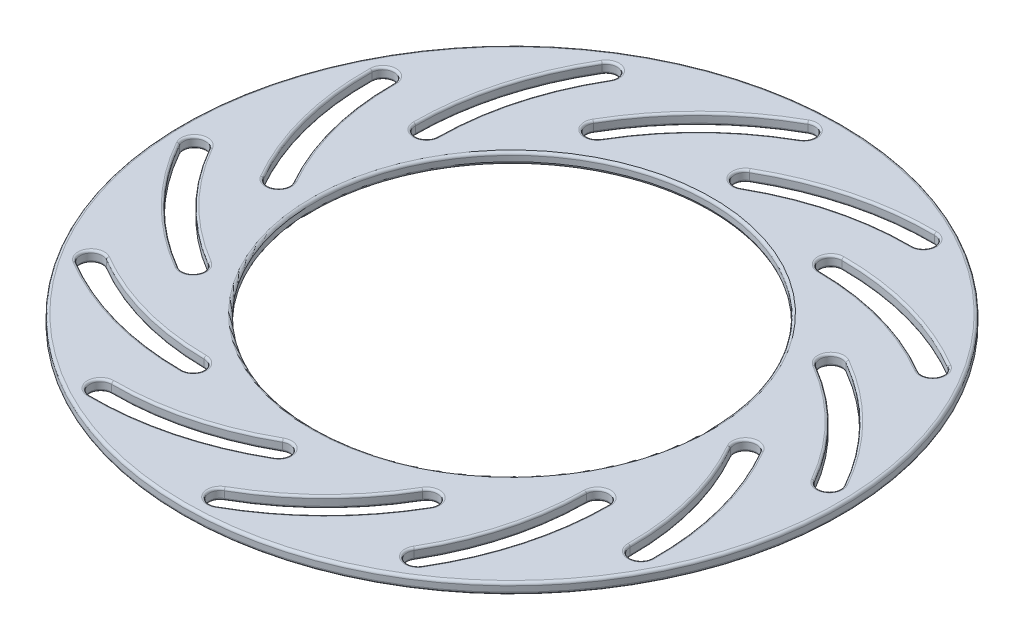
SolidWorks part; units mm, degrees
material "Сталь 3 ГОСТ 380-94"
ref_plane "Спереди" through (0, 0, 0) normal (0, 0, 1) x (1, 0, 0)
ref_plane "Сверху" through (0, 0, 0) normal (0, 1, 0) x (1, 0, 0)
ref_plane "Справа" through (0, 0, 0) normal (1, 0, 0) x (0, 0, -1)
sketch "Эскиз1" plane through (0, 0, 0) normal (0, 1, 0) x (1, 0, 0)
  circle A0 centre (0, 0) radius 36
  circle A1 centre (0, 0) radius 60
  dimension "D1" = 72
  dimension "D2" = 120
extrude "Бобышка-Вытянуть1" add sketch "Эскиз1" along normal mid plane 2
sketch "Эскиз2" plane through (0, 1, 0) normal (0, 1, 0) x (1, 0, 0)
  line L0 (0, 0) -> (0, 69.7316) construction
  line L1 (0, 42.5) -> (9.5343, 48.0046) construction
  circle A0 centre (0, 0) radius 42.5 construction
  circle A1 centre (0, 0) radius 55.5 construction
  arc A2 (-1, 44.2321) -> (0.9908, 40.7627) centre (0, 42.5) ccw
  circle A3 centre (25, -0.8013) radius 50 construction
  arc A4 (25.6774, 47.194) -> (25.7223, 51.1937) centre (25.6945, 49.1939) ccw
  arc A5 (0.9908, 40.7627) -> (25.6774, 47.194) centre (25.2566, -1.7863) cw
  arc A6 (-1, 44.2321) -> (25.7223, 51.1937) centre (25, -0.8013) cw
  dimension "D1" = 85
  dimension "D2" = 111
  dimension "D3" = 4
  dimension "D4" = 100
  dimension "D5" = 60
extrude "Вырез-Вытянуть1" cut sketch "Эскиз2" against normal through all
fillet "Скругление2" radius 0.4 8 edges at (27.6944, -1, -49.1714) (12.908, -1, -45.6137) (-1.7347, -1, -41.5046) (27.6944, 1, -49.1714) (12.908, 1, -45.6137) (-1.7347, 1, -41.5046) (11.8906, -1, -49.5191) (11.8906, 1, -49.5191)
pattern_circular "Круговой массив1" count 12 over 360 about axis through (0, 0, 0) along (0, 1, 0) of "Вырез-Вытянуть1", "Скругление2"
fillet "Скругление1" radius 0.5 4 edges at (0, -1, 60) (0, 1, 60) (0, -1, 36) (0, 1, 36)
